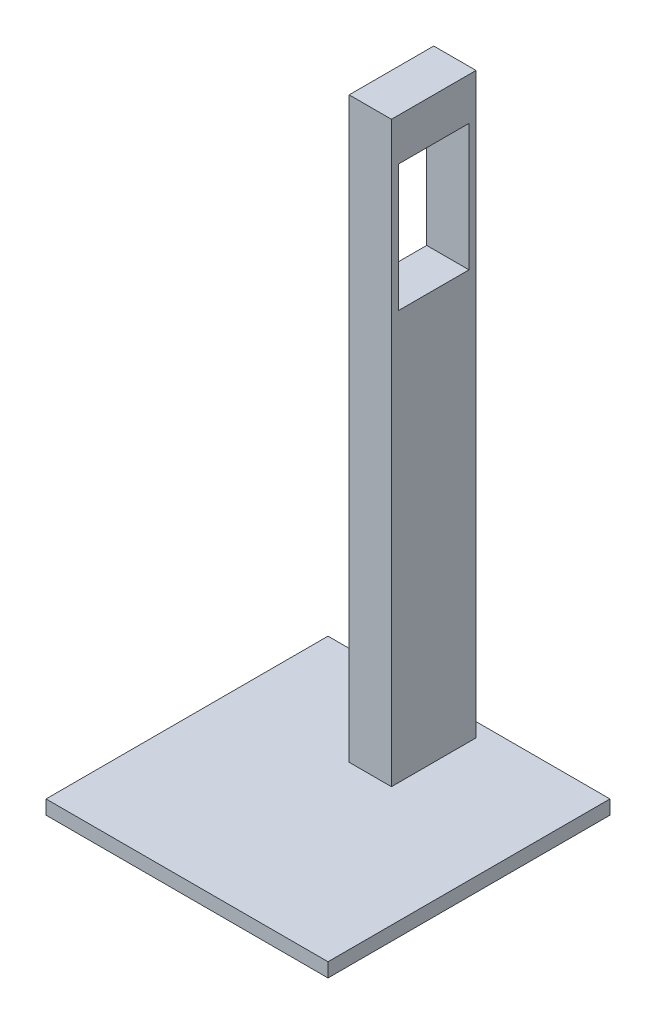
SolidWorks part; units mm, degrees
ref_plane "Front Plane" through (0, 0, 0) normal (0, 0, 1) x (1, 0, 0)
ref_plane "Top Plane" through (0, 0, 0) normal (0, 1, 0) x (1, 0, 0)
ref_plane "Right Plane" through (0, 0, 0) normal (1, 0, 0) x (0, 0, -1)
sketch "Sketch1" plane through (0, 0, 0) normal (0, 1, 0) x (1, 0, 0)
  line L1 (-25.4, -25.4) -> (25.4, -25.4)
  line L2 (-25.4, -25.4) -> (-25.4, 25.4)
  line L3 (-25.4, 25.4) -> (25.4, 25.4)
  line L4 (25.4, -25.4) -> (25.4, 25.4)
  line L5 (-25.4, -25.4) -> (25.4, 25.4) construction
  line L6 (-25.4, 25.4) -> (25.4, -25.4) construction
  point P0 (0, 0)
  dimension "D1" = 50.8
  dimension "D2" = 50.8
extrude "Boss-Extrude1" add sketch "Sketch1" along normal blind 2.54
sketch "Sketch2" plane through (0, 2.54, 0) normal (0, 1, 0) x (1, 0, 0)
  line L1 (-3.81, 22.86) -> (3.81, 22.86)
  line L2 (-3.81, 22.86) -> (-3.81, 7.62)
  line L3 (-3.81, 7.62) -> (3.81, 7.62)
  line L4 (3.81, 22.86) -> (3.81, 7.62)
  line L5 (-3.81, 22.86) -> (3.81, 7.62) construction
  line L6 (-3.81, 7.62) -> (3.81, 22.86) construction
  point P0 (0, 15.24)
  dimension "D1" = 15.24
  dimension "D2" = 15.24
  dimension "D3" = 7.62
extrude "Boss-Extrude2" add sketch "Sketch2" along normal blind 104.14
sketch "Sketch3" plane through (-3.81, 0, 0) normal (-1, 0, 0) x (0, 0, 1)
  line L0 (-15.24, 99.06) -> (-15.24, 106.68) construction
  line L1 (-21.59, 76.2) -> (-8.89, 76.2)
  line L2 (-21.59, 76.2) -> (-21.59, 99.06)
  line L3 (-21.59, 99.06) -> (-8.89, 99.06)
  line L4 (-8.89, 76.2) -> (-8.89, 99.06)
  line L5 (-21.59, 76.2) -> (-8.89, 99.06) construction
  line L6 (-21.59, 99.06) -> (-8.89, 76.2) construction
  line L7 (-22.86, 106.68) -> (-7.62, 106.68) construction
  point P0 (-15.24, 87.63)
  dimension "D1" = 7.62
  dimension "D2" = 22.86
  dimension "D3" = 12.7
extrude "Cut-Extrude1" cut sketch "Sketch3" against normal through all
